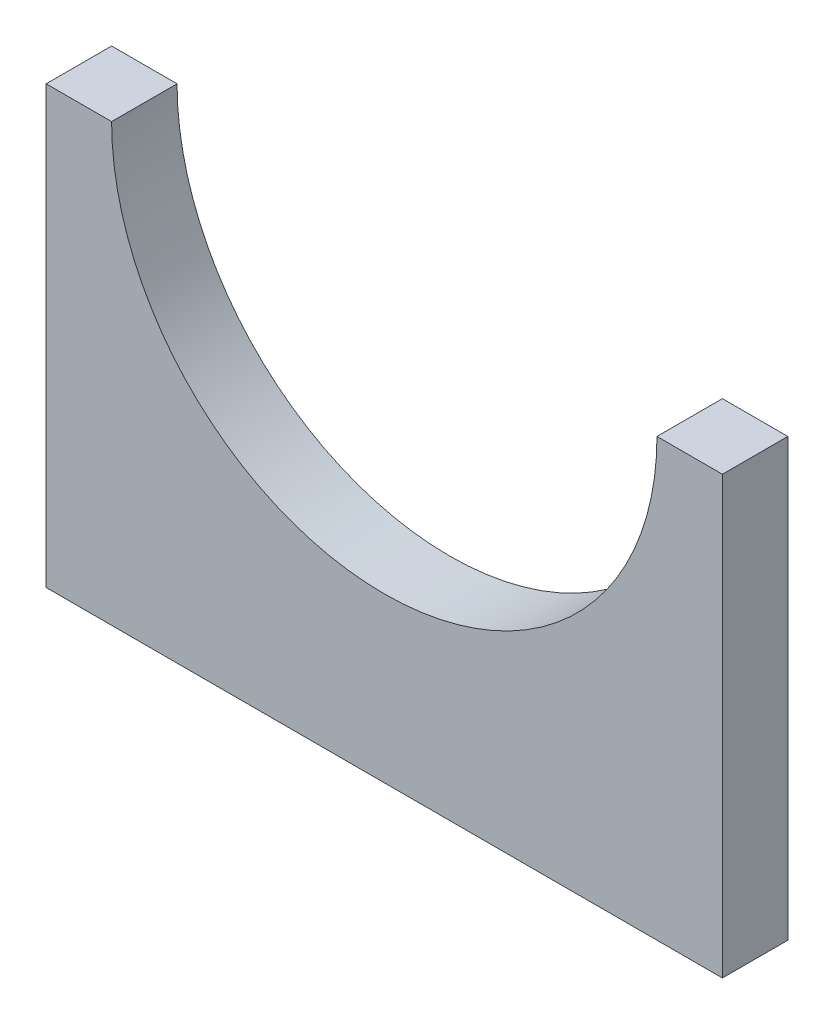
SolidWorks part; units mm, degrees
ref_plane "Front Plane" through (0, 0, 0) normal (0, 0, 1) x (1, 0, 0)
ref_plane "Top Plane" through (0, 0, 0) normal (0, 1, 0) x (1, 0, 0)
ref_plane "Right Plane" through (0, 0, 0) normal (1, 0, 0) x (0, 0, -1)
sketch "Sketch1" plane through (0, 0, 0) normal (0, 0, 1) x (1, 0, 0)
  line L0 (0, 16.6293) -> (0, -9.6904) construction
  line L1 (-15.5, 0) -> (-12.5, 0)
  line L2 (15.5, 0) -> (15.5, -20)
  line L3 (15.5, -20) -> (-15.5, -20)
  line L4 (-15.5, -20) -> (-15.5, 0)
  line L5 (12.5, 0) -> (15.5, 0)
  arc A0 (-12.5, 0) -> (12.5, 0) centre (0, 0) ccw
  point P5 (0, 0)
  dimension "D1" = 25
  dimension "D3" = 20
  dimension "D2" = 15.5
extrude "Boss-Extrude1" add sketch "Sketch1" along normal mid plane 3
